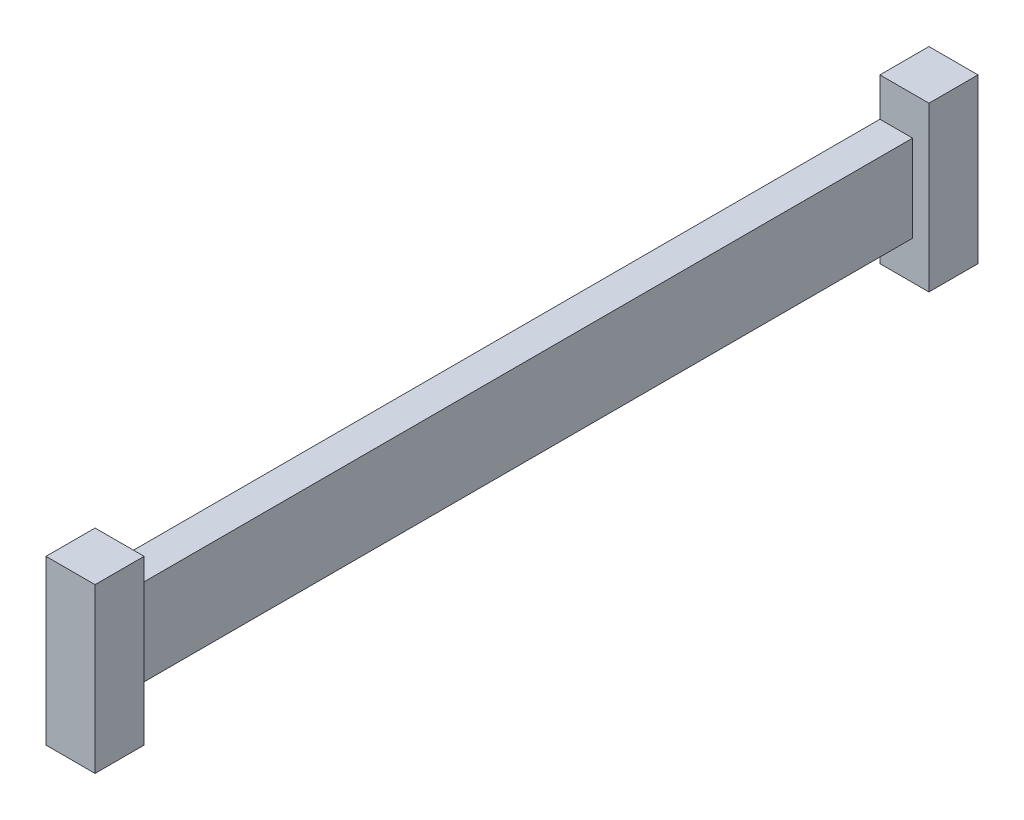
SolidWorks part; units mm, degrees
ref_plane "Front Plane" through (0, 0, 0) normal (0, 0, 1) x (1, 0, 0)
ref_plane "Top Plane" through (0, 0, 0) normal (0, 1, 0) x (1, 0, 0)
ref_plane "Right Plane" through (0, 0, 0) normal (1, 0, 0) x (0, 0, -1)
sketch "Sketch1" plane through (0, 0, 0) normal (1, 0, 0) x (0, 0, -1)
  line L0 (0, 0) -> (0, 10)
  line L1 (0, 10) -> (3, 10)
  line L2 (3, 10) -> (3, 7.65)
  line L3 (3, 7.65) -> (51, 7.65)
  line L4 (51, 7.65) -> (51, 10)
  line L5 (51, 10) -> (54, 10)
  line L6 (54, 10) -> (54, 0)
  line L7 (54, 0) -> (51, 0)
  line L8 (51, 0) -> (51, 2.35)
  line L9 (51, 2.35) -> (3, 2.35)
  line L10 (3, 2.35) -> (3, 0)
  line L11 (3, 0) -> (0, 0)
  dimension "D1" = 10
  dimension "D2" = 3
  dimension "D3" = 48
  dimension "D4" = 5.3
extrude "Boss-Extrude1" add sketch "Sketch1" along normal blind 3
sketch "Sketch2" plane through (3, 0, 0) normal (1, 0, 0) x (0, 0, -1)
  line L0 (3, 2.35) -> (51, 2.35) construction
  line L1 (3, 7.65) -> (51, 7.65)
  line L2 (3, 7.65) -> (3, 2.35)
  line L3 (3, 2.35) -> (51, 2.35)
  line L4 (51, 7.65) -> (51, 2.35)
extrude "Cut-Extrude1" cut sketch "Sketch2" against normal blind 1
